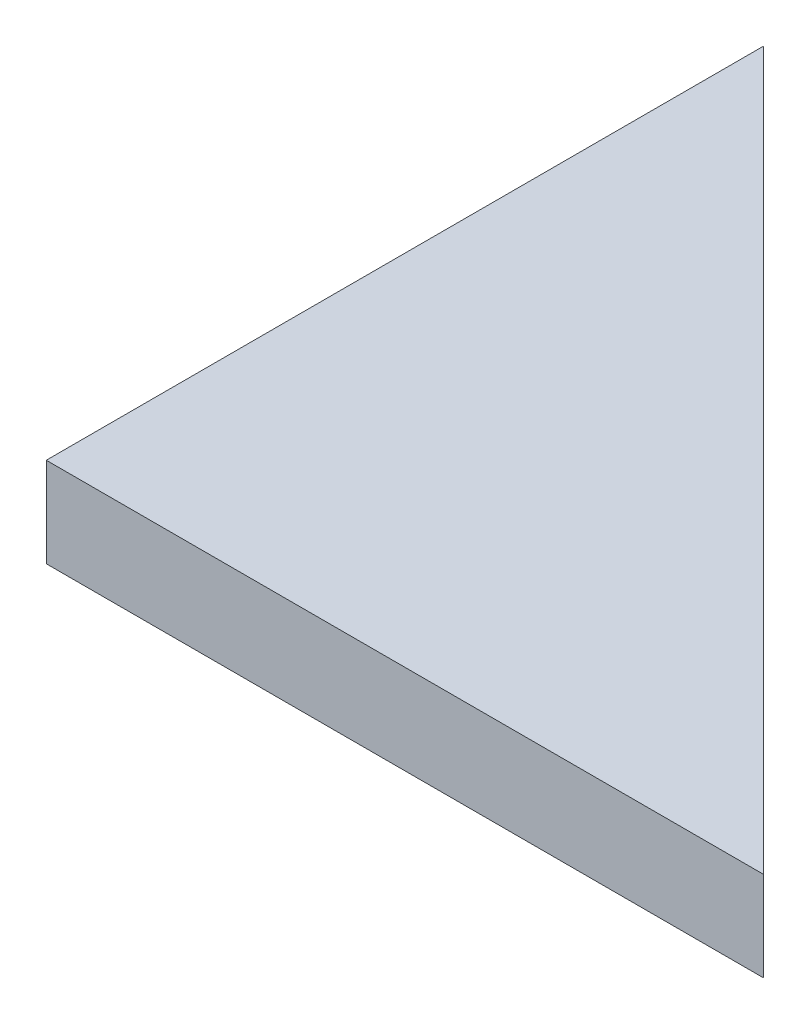
SolidWorks part; units mm, degrees
ref_plane "Front Plane" through (0, 0, 0) normal (0, 0, 1) x (1, 0, 0)
ref_plane "Top Plane" through (0, 0, 0) normal (0, 1, 0) x (1, 0, 0)
ref_plane "Right Plane" through (0, 0, 0) normal (1, 0, 0) x (0, 0, -1)
sketch "Sketch1" plane through (0, 0, 0) normal (0, 1, 0) x (1, 0, 0)
  line L0 (0, 0) -> (25.4, 0)
  line L1 (25.4, 0) -> (0, 25.4)
  line L2 (0, 25.4) -> (0, 0)
  dimension "D1" = 25.4
  dimension "D2" = 25.4
extrude "Boss-Extrude1" add sketch "Sketch1" along normal blind 3.175
